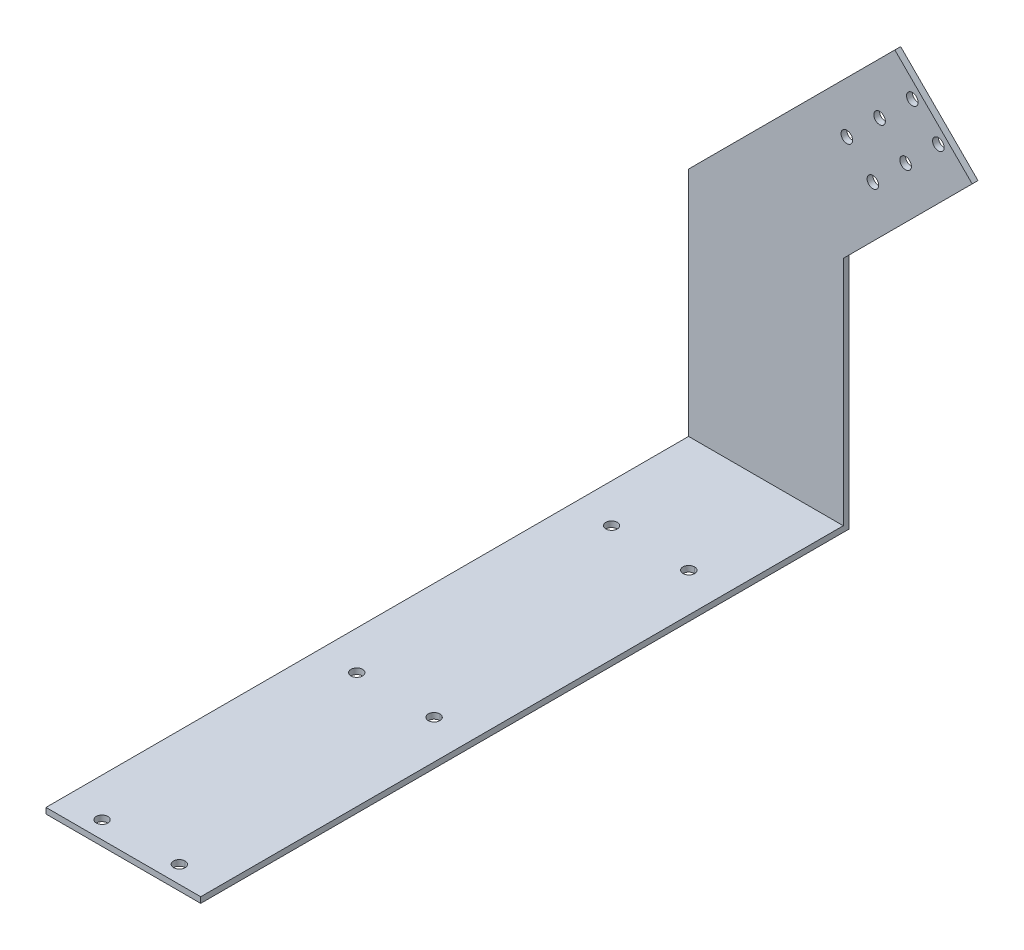
SolidWorks part; units mm, degrees
material "Malleable Cast Iron"
ref_plane "Front Plane" through (0, 0, 0) normal (0, 0, 1) x (1, 0, 0)
ref_plane "Top Plane" through (0, 0, 0) normal (0, 1, 0) x (1, 0, 0)
ref_plane "Right Plane" through (0, 0, 0) normal (1, 0, 0) x (0, 0, -1)
sketch "Sketch1" plane through (0, 0, 0) normal (0, 0, 1) x (1, 0, 0)
  line L0 (-2155.317, 3225.8) -> (3592.0469, 8973.1639)
  line L1 (2155.317, -3225.8) -> (-2155.317, -3225.8)
  line L2 (2155.317, -3225.8) -> (2155.317, 3225.8)
  line L4 (-2155.317, -3225.8) -> (-2155.317, 3225.8)
  line L5 (2155.317, -3225.8) -> (-2155.317, 3225.8) construction
  line L6 (2155.317, 3225.8) -> (-2155.317, -3225.8) construction
  line L7 (2155.317, 3225.8) -> (5747.4194, 6817.9024)
  line L8 (3592.0469, 8973.1639) -> (5747.4194, 6817.9024)
  line L9 (4669.7332, 7895.5332) -> (164.403, 3389.9708) construction
  circle A7 centre (4804.8334, 7304.2547) radius 161.29
  circle A8 centre (3892.4393, 6391.8607) radius 161.29
  circle A9 centre (2980.0453, 5479.4667) radius 161.29
  circle A10 centre (2253.7537, 6205.7208) radius 161.29
  circle A11 centre (3166.1007, 7118.1619) radius 161.29
  circle A12 centre (4078.4478, 8030.6029) radius 161.29
  point P0 (0, 0)
  dimension "D8" = 322.58
  dimension "D9" = 322.58
  dimension "D10" = 3
  dimension "D11" = 1290.32
  dimension "D1" = 4310.634
  dimension "D2" = 6451.6
  dimension "D3" = 135
  dimension "D4" = 135
  dimension "D5" = 8128
  dimension "D6" = 5080
  dimension "D7" = 3048.0785
  dimension "D15" = 1010.412
extrude "Boss-Extrude1" add sketch "Sketch1" along normal blind 161.29
ref_plane "Plane1" through (0, -3225.8, 0) normal (0, -1, 0) x (-1, 0, 0)
sketch "Sketch3" plane through (0, -3225.8, 0) normal (0, -1, 0) x (-1, 0, 0)
  line L0 (2155.317, 0) -> (-2155.317, 0) construction
  line L1 (-2155.317, 0) -> (2155.317, 0)
  line L2 (-2155.317, 0) -> (-2155.317, -18064.48)
  line L3 (-2155.317, -18064.48) -> (2155.317, -18064.48)
  line L4 (2155.317, 0) -> (2155.317, -18064.48)
  line L5 (2155.317, -161.29) -> (2155.317, 0) construction
  line L6 (2155.317, -161.29) -> (-2155.317, -161.29) construction
  line L8 (0, -18064.48) -> (0, -242.9474) construction
  circle A0 centre (-1077.595, -17580.61) radius 161.29
  circle A2 centre (-1077.595, -10483.85) radius 161.29
  circle A3 centre (-1075.055, -17580.61) radius 161.29
  circle A4 centre (-1075.055, -10483.85) radius 161.29
  circle A5 centre (-1075.055, -3387.09) radius 161.29
  circle A6 centre (-1077.595, -10483.85) radius 161.29
  circle A7 centre (-1077.595, -3387.09) radius 161.29
  circle A8 centre (1075.055, -3387.09) radius 161.29
  circle A9 centre (1077.595, -10483.85) radius 161.29
  circle A10 centre (1077.595, -17580.61) radius 161.29
  point P0 (0, 0)
  point P14 (0, 0)
  point P34 (0, 0)
  point P35 (0, 0)
  dimension "D3" = 322.58
  dimension "D4" = 2
  dimension "D5" = 322.58
  dimension "D6" = 3
  dimension "D7" = 3225.8
  dimension "D8" = 7096.76
  dimension "D9" = 7096.76
  dimension "D1" = 4310.634
  dimension "D2" = 18064.48
  dimension "D10" = 2150.11
  dimension "D12" = 1077.722
extrude "Boss-Extrude3" add sketch "Sketch3" along normal blind 161.29
scale "Scale1" bodies to scale 103 scale about centroid uniform scaling yes scale factor 0.03937
